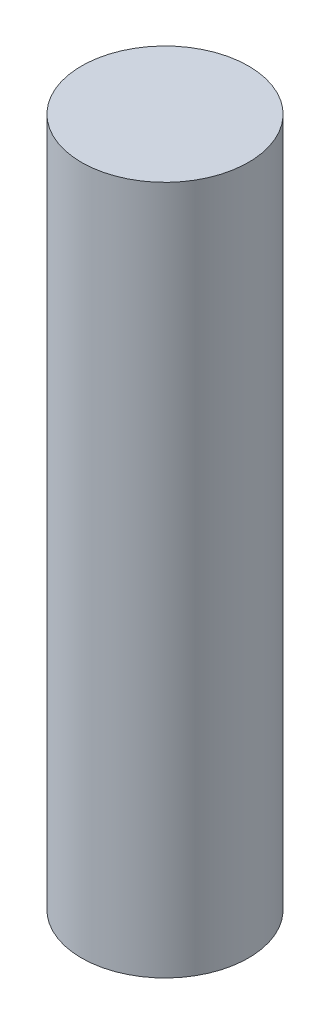
SolidWorks part; units mm, degrees
ref_plane "Front Plane" through (0, 0, 0) normal (0, 0, 1) x (1, 0, 0)
ref_plane "Top Plane" through (0, 0, 0) normal (0, 1, 0) x (1, 0, 0)
ref_plane "Right Plane" through (0, 0, 0) normal (1, 0, 0) x (0, 0, -1)
sketch "Sketch1" plane through (0, 0, 0) normal (0, 1, 0) x (1, 0, 0)
  circle A0 centre (0, 0) radius 4
  dimension "D1" = 8
extrude "Boss-Extrude1" add sketch "Sketch1" along normal blind 33 contours A0
